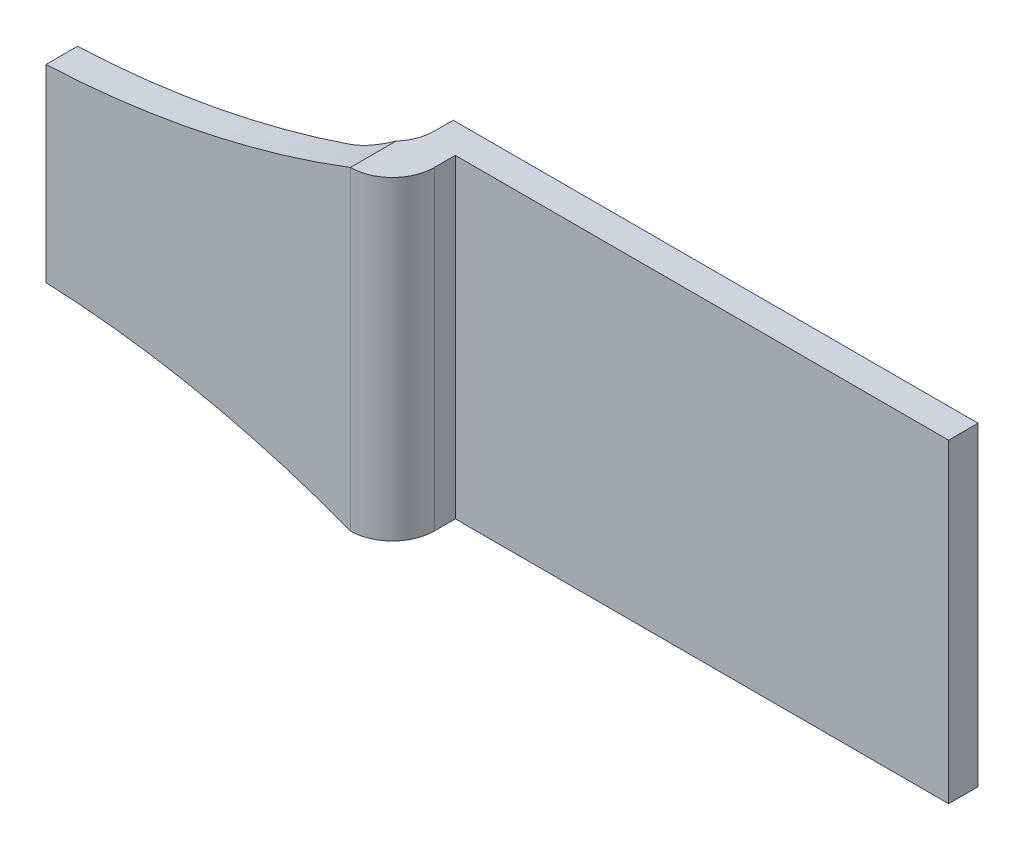
SolidWorks part; units mm, degrees
ref_plane "Alzado" through (0, 0, 0) normal (0, 0, 1) x (1, 0, 0)
ref_plane "Planta" through (0, 0, 0) normal (0, 1, 0) x (1, 0, 0)
ref_plane "Vista lateral" through (0, 0, 0) normal (1, 0, 0) x (0, 0, -1)
sketch "Croquis1" plane through (0, 0, 0) normal (0, 0, 1) x (1, 0, 0)
  line L1 (-79.1958, 25.3827) -> (-54.1958, 25.3827)
  line L2 (-79.1958, 25.3827) -> (-79.1958, 10.3827)
  line L3 (-79.1958, 10.3827) -> (-54.1958, 10.3827)
  line L4 (-54.1958, 25.3827) -> (-54.1958, 10.3827)
  dimension "D1" = 25
  dimension "D2" = 15
extrude "Saliente-Extruir1" add sketch "Croquis1" along normal blind 1.4
sketch "Croquis3" plane through (0, 10.3827, 0) normal (0, -1, 0) x (1, 0, 0)
  line L0 (-79.1958, 1.4) -> (-79.1958, 2.9)
  line L1 (-79.1958, 2.9) -> (-94.1958, 2.9)
  line L2 (-94.1958, 2.9) -> (-94.1958, 4.4)
  line L3 (-79.1958, 1.4) -> (-77.6958, 1.4)
  line L4 (-94.1958, 4.4) -> (-77.6958, 4.4)
  line L5 (-77.6958, 4.4) -> (-77.6958, 1.4)
  line L6 (-79.1958, 1.4) -> (-54.1958, 1.4) construction
  dimension "D1" = 1.5
  dimension "D2" = 16.5
  dimension "D3" = 1.5
  dimension "D4" = 1.5
extrude "Saliente-Extruir2" add sketch "Croquis3" against normal up to vertex (15 mm away)
fillet "Redondeo1" radius 2 2 edges at (-79.1958, 17.8827, 2.9) (-77.6958, 17.8827, 4.4)
sketch "Croquis4" plane through (0, 0, 4.4) normal (0, 0, 1) x (1, 0, 0)
  line L1 (-94.1958, 25.3827) -> (-94.1958, 10.3827) construction
  line L2 (-94.1958, 17.8827) -> (-79.6958, 17.8827) construction
  line L3 (-79.6958, 10.3827) -> (-79.6958, 25.3827) construction
  line L4 (-79.6958, 25.3827) -> (-94.1958, 25.3827)
  line L5 (-94.1958, 25.3827) -> (-94.1958, 22.3827)
  line L6 (-94.1958, 13.3827) -> (-94.1958, 10.3827)
  line L7 (-94.1958, 10.3827) -> (-79.6958, 10.3827)
  arc A0 (-94.1958, 13.3827) -> (-79.6958, 10.3827) centre (-96.1499, -32.6039) cw
  arc A1 (-94.1958, 22.3827) -> (-79.6958, 25.3827) centre (-96.1499, 68.3692) ccw
extrude "Cortar-Extruir1" cut sketch "Croquis4" against normal up to vertex
